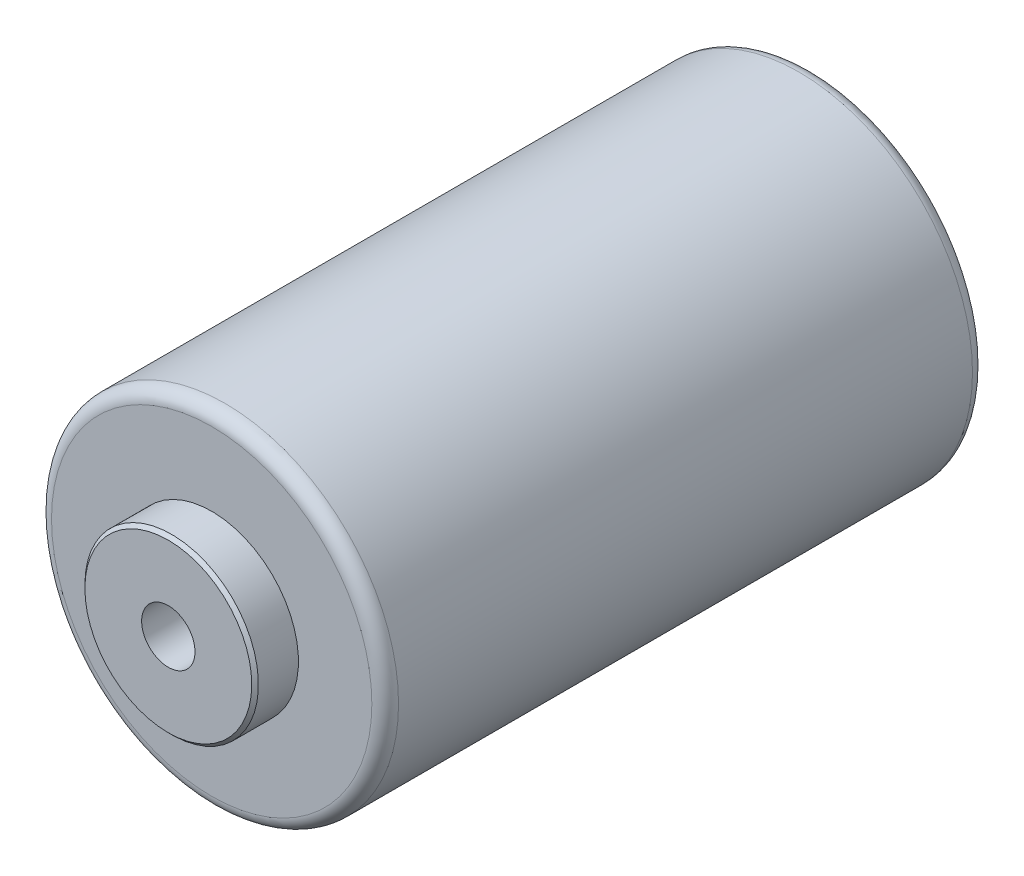
SolidWorks part; units mm, degrees
material "6061 slitina"
ref_plane "Horní rovina" through (0, 0, 0) normal (0, 0, 1) x (1, 0, 0)
ref_plane "Přední rovina" through (0, 0, 0) normal (0, 1, 0) x (1, 0, 0)
ref_plane "Pravá rovina" through (0, 0, 0) normal (1, 0, 0) x (0, 0, -1)
sketch "Skica1" plane through (0, 0, 0) normal (0, 0, 1) x (1, 0, 0)
  circle A0 centre (0, 0) radius 26
  dimension "D1" = 52
extrude "Přidat vysunutím1" add sketch "Skica1" along normal blind 90
fillet "Zaoblit1" radius 2 2 edges at (26, 0, 0) (26, 0, 90)
sketch "Skica2" plane through (0, 0, 0) normal (0, 0, -1) x (-1, 0, 0)
  circle A0 centre (0, 0) radius 13
  dimension "D1" = 26
extrude "Přidat vysunutím2" add sketch "Skica2" along normal blind 6.5
sketch "Skica3" plane through (0, 0, -6.5) normal (0, 0, -1) x (-1, 0, 0)
  circle A0 centre (0, 0) radius 4
  dimension "D1" = 8
extrude "Přidat vysunutím3" [suppressed] add sketch "Skica3" along normal blind 20
sketch "Skica4" plane through (0, 0, 0) normal (0, 0, -1) x (-1, 0, 0)
  circle A0 centre (0, 0) radius 17.5 construction
  circle A1 centre (-17.5, 0) radius 1.6
  circle A2 centre (0, 17.5) radius 1.6
  circle A3 centre (17.5, 0) radius 1.6
  circle A4 centre (0, -17.5) radius 1.6
  dimension "D1" = 35
  dimension "D2" = 3.2
  dimension "D3" = 3.2
  dimension "D4" = 3.2
  dimension "D5" = 3.2
extrude "Odebrat vysunutím1" cut sketch "Skica4" against normal blind 10
sketch "Skica5" plane through (0, 0, 90) normal (0, 0, 1) x (1, 0, 0)
  circle A0 centre (0, 0) radius 13
  dimension "D1" = 26
extrude "Přidat vysunutím4" add sketch "Skica5" along normal blind 6.5
sketch "Skica6" plane through (0, 0, 96.5) normal (0, 0, 1) x (1, 0, 0)
  circle A0 centre (0, 0) radius 4
  dimension "D1" = 8
extrude "Přidat vysunutím5" [suppressed] add sketch "Skica6" along normal blind 25
chamfer "Zkosení1" distance 0.5 angle 45 2 edges at (-13, 0, -6.5) (13, 0, 96.5)
chamfer "Zkosení2" [suppressed] distance 0.5 angle 45
sketch "Skica7" [suppressed] plane through (0, 0, -26.5) normal (0, 0, -1) x (-1, 0, 0)
  line L0 (-1.9365, 3.5) -> (1.9365, 3.5)
  circle A0 centre (0, 0) radius 4 construction
  arc A1 (1.9365, 3.5) -> (-1.9365, 3.5) centre (0, 0) ccw
  dimension "D1" = 3.5
extrude "Odebrat vysunutím2" [suppressed] cut sketch "Skica7" against normal blind 19
sketch "Skica8" plane through (0, 0, -6.5) normal (0, 0, -1) x (-1, 0, 0)
  circle A0 centre (0, 0) radius 4
  dimension "D1" = 8
extrude "Odebrat vysunutím3" cut sketch "Skica8" against normal through all
